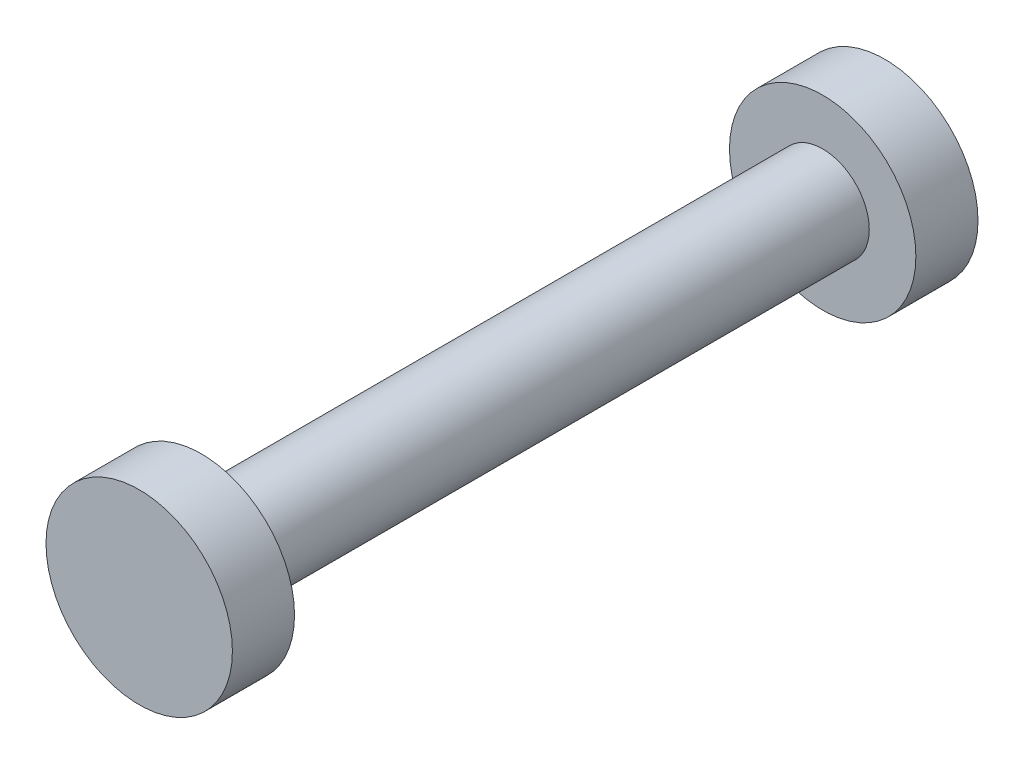
SolidWorks part; units mm, degrees
ref_plane "Front Plane" through (0, 0, 0) normal (0, 0, 1) x (1, 0, 0)
ref_plane "Top Plane" through (0, 0, 0) normal (0, 1, 0) x (1, 0, 0)
ref_plane "Right Plane" through (0, 0, 0) normal (1, 0, 0) x (0, 0, -1)
sketch "Sketch1" plane through (0, 0, 0) normal (0, 0, 1) x (1, 0, 0)
  circle A0 centre (0, 0) radius 0.75
extrude "Boss-Extrude1" add sketch "Sketch1" along normal mid plane 10
sketch "Sketch2" plane through (0, 0, 5) normal (0, 0, 1) x (1, 0, 0)
  circle A0 centre (0, 0) radius 1.5
extrude "Boss-Extrude2" add sketch "Sketch2" along normal blind 1
sketch "Sketch3" plane through (0, 0, -5) normal (0, 0, -1) x (-1, 0, 0)
  circle A0 centre (0, 0) radius 1.5
extrude "Boss-Extrude3" add sketch "Sketch3" along normal blind 1
